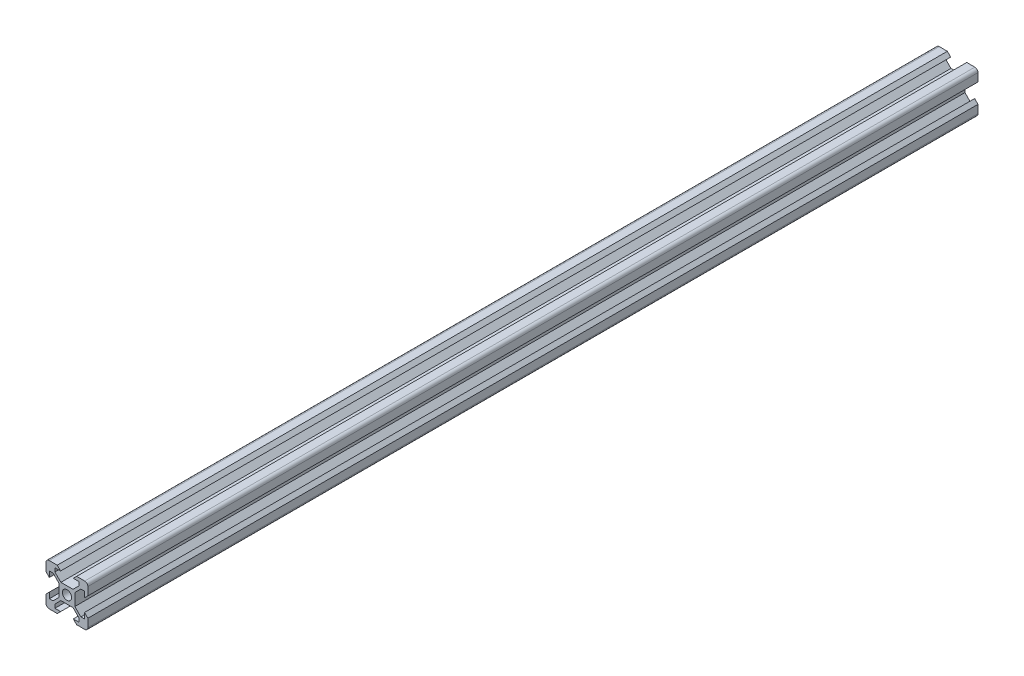
SolidWorks part; units mm, degrees
ref_plane "Front Plane" through (0, 0, 0) normal (0, 0, 1) x (1, 0, 0)
ref_plane "Top Plane" through (0, 0, 0) normal (0, 1, 0) x (1, 0, 0)
ref_plane "Right Plane" through (0, 0, 0) normal (1, 0, 0) x (0, 0, -1)
sketch "Sketch1" plane through (0, 0, 0) normal (0, 0, 1) x (1, 0, 0)
  line L0 (-5.7847, 7.544) -> (-11.512, 13.2713)
  line L1 (-7.544, 7.544) -> (7.544, 7.544)
  line L2 (-7.544, 7.544) -> (-7.544, -7.544)
  line L3 (-7.544, -7.544) -> (7.544, -7.544)
  line L4 (7.544, 7.544) -> (7.544, -7.544)
  line L5 (-7.544, 7.544) -> (7.544, -7.544) construction
  line L6 (-7.544, -7.544) -> (7.544, 7.544) construction
  line L7 (-11.512, 13.2713) -> (-11.512, 16.8)
  line L8 (-11.512, 16.8) -> (-6.052, 16.8)
  line L9 (-6.052, 16.8) -> (-9.252, 20)
  line L10 (-9.252, 20) -> (-17, 20)
  line L11 (-20, 17) -> (-20, 9.252)
  line L12 (-20, 9.252) -> (-16.8, 6.052)
  line L13 (-16.8, 6.052) -> (-16.8, 11.512)
  line L14 (-16.8, 11.512) -> (-13.2713, 11.512)
  line L15 (-13.2713, 11.512) -> (-7.544, 5.7847)
  line L16 (-19.1213, 19.1213) -> (0, 0) construction
  line L17 (13.2713, 11.512) -> (16.8, 11.512)
  line L18 (20, 9.252) -> (20, 17)
  line L19 (17, 20) -> (9.252, 20)
  line L20 (9.252, 20) -> (6.052, 16.8)
  line L21 (6.052, 16.8) -> (11.512, 16.8)
  line L22 (11.512, 16.8) -> (11.512, 13.2713)
  line L23 (11.512, 13.2713) -> (5.7847, 7.544)
  line L24 (7.544, 5.7847) -> (13.2713, 11.512)
  line L25 (16.8, 11.512) -> (16.8, 6.052)
  line L26 (16.8, 6.052) -> (20, 9.252)
  line L27 (19.1213, 19.1213) -> (0, 0) construction
  line L28 (11.512, -13.2713) -> (11.512, -16.8)
  line L29 (9.252, -20) -> (17, -20)
  line L30 (20, -17) -> (20, -9.252)
  line L31 (20, -9.252) -> (16.8, -6.052)
  line L32 (16.8, -6.052) -> (16.8, -11.512)
  line L33 (16.8, -11.512) -> (13.2713, -11.512)
  line L34 (13.2713, -11.512) -> (7.544, -5.7847)
  line L35 (5.7847, -7.544) -> (11.512, -13.2713)
  line L36 (11.512, -16.8) -> (6.052, -16.8)
  line L37 (6.052, -16.8) -> (9.252, -20)
  line L38 (19.1213, -19.1213) -> (0, 0) construction
  line L39 (-13.2713, -11.512) -> (-16.8, -11.512)
  line L40 (-20, -9.252) -> (-20, -17)
  line L41 (-17, -20) -> (-9.252, -20)
  line L42 (-9.252, -20) -> (-6.052, -16.8)
  line L43 (-6.052, -16.8) -> (-11.512, -16.8)
  line L44 (-11.512, -16.8) -> (-11.512, -13.2713)
  line L45 (-11.512, -13.2713) -> (-5.7847, -7.544)
  line L46 (-7.544, -5.7847) -> (-13.2713, -11.512)
  line L47 (-16.8, -11.512) -> (-16.8, -6.052)
  line L48 (-16.8, -6.052) -> (-20, -9.252)
  line L49 (-19.1213, -19.1213) -> (0, 0) construction
  circle A0 centre (0, 0) radius 4.4
  arc A1 (-17, 20) -> (-20, 17) centre (-17, 17) ccw
  arc A2 (20, 17) -> (17, 20) centre (17, 17) ccw
  arc A3 (17, -20) -> (20, -17) centre (17, -17) ccw
  arc A4 (-20, -17) -> (-17, -20) centre (-17, -17) ccw
  point P66 (0, 0)
  dimension "D1" = 8.8
  dimension "D8" = 3
  dimension "D2" = 15.088
  dimension "D3" = 2.488
  dimension "D4" = 8.488
  dimension "D5" = 3.2
  dimension "D6" = 20
  dimension "D7" = 15.2
  dimension "D9" = 4
extrude "Boss-Extrude1" add sketch "Sketch1" along normal mid plane 850 contours L10 A1 L11 L12 L13 L14 L15 L2 L1 L0 L7 L8 L9 | L18 A2 L19 L20 L21 L22 L23 L1 L4 L24 L17 L25 L26 | L40 A4 L41 L42 L43 L44 L45 L3 L2 L46 L39 L47 L48 | L29 A3 L30 L31 L32 L33 L34 L4 L3 L35 L28 L36 L37 | L4 L1 L2 L3 A0
equation "\"longitud\"= 800"
